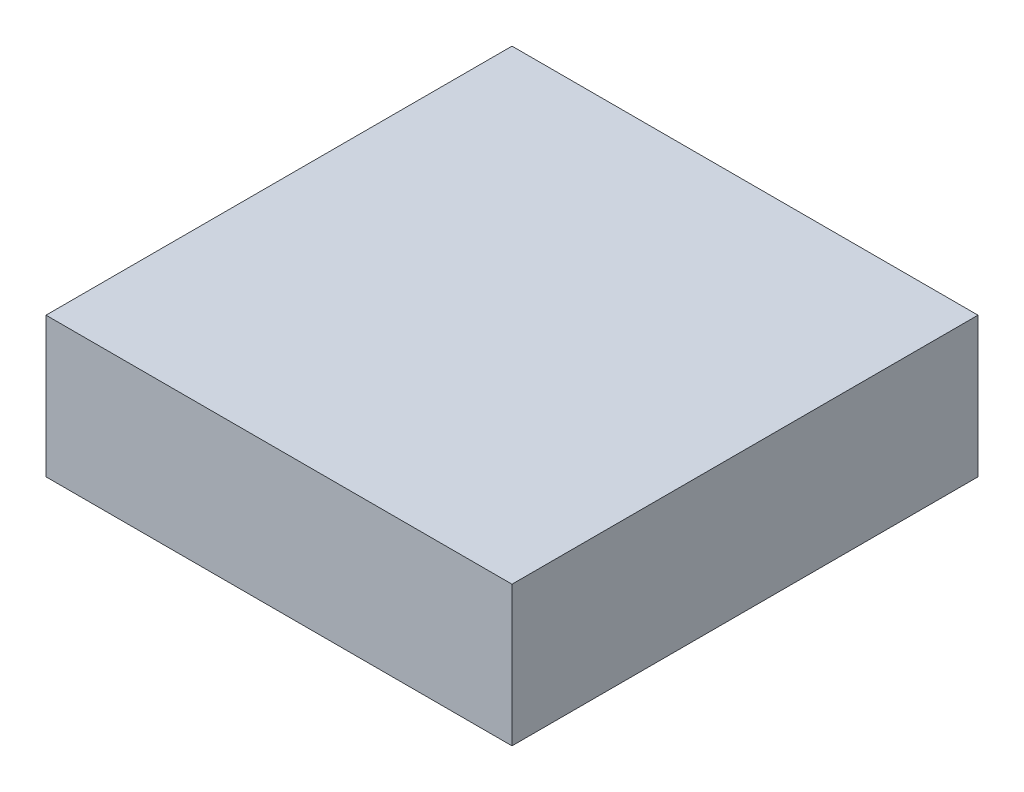
SolidWorks part; units mm, degrees
ref_plane "Front Plane" through (0, 0, 0) normal (0, 0, 1) x (1, 0, 0)
ref_plane "Top Plane" through (0, 0, 0) normal (0, 1, 0) x (1, 0, 0)
ref_plane "Right Plane" through (0, 0, 0) normal (1, 0, 0) x (0, 0, -1)
sketch "Sketch1" plane through (0, 0, 0) normal (0, 1, 0) x (1, 0, 0)
  line L1 (-20.3, -20.3) -> (20.3, -20.3)
  line L2 (-20.3, -20.3) -> (-20.3, 20.3)
  line L3 (-20.3, 20.3) -> (20.3, 20.3)
  line L4 (20.3, -20.3) -> (20.3, 20.3)
  line L5 (-20.3, -20.3) -> (20.3, 20.3) construction
  line L6 (-20.3, 20.3) -> (20.3, -20.3) construction
  point P0 (0, 0)
  dimension "D1" = 40.6
  dimension "D2" = 40.6
extrude "Boss-Extrude1" add sketch "Sketch1" along normal blind 12.2
